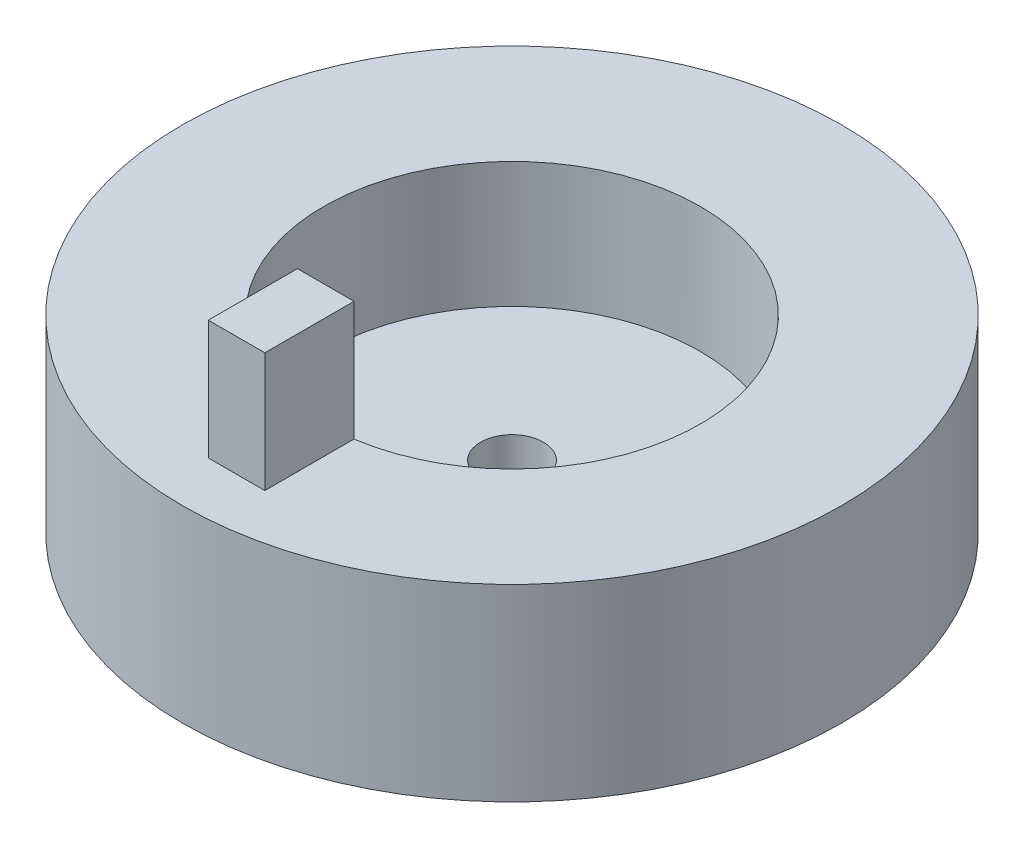
SolidWorks part; units mm, degrees
ref_plane "Front" through (0, 0, 0) normal (0, 0, 1) x (1, 0, 0)
ref_plane "Top" through (0, 0, 0) normal (0, 1, 0) x (1, 0, 0)
ref_plane "Right" through (0, 0, 0) normal (1, 0, 0) x (0, 0, -1)
sketch "Skizze1" plane through (0, 0, 0) normal (0, 1, 0) x (1, 0, 0)
  circle A0 centre (0, 0) radius 30
  circle A1 centre (0, 0) radius 52.5
  dimension "D1" = 60
  dimension "D2" = 105
extrude "Aufsatz-Linear austragen1" add sketch "Skizze1" along normal blind 20
sketch "Skizze2" plane through (0, 0, 0) normal (0, -1, 0) x (1, 0, 0)
  circle A0 centre (0, 0) radius 52.5
  circle A1 centre (0, 0) radius 5
  circle A2 centre (0, 0) radius 52.5 construction
  dimension "D1" = 10
extrude "Aufsatz-Linear austragen2" add sketch "Skizze2" along normal blind 10
sketch "Skizze3" plane through (0, 20, 0) normal (0, 1, 0) x (1, 0, 0)
  line L0 (0, 0) -> (0, -64.4242) construction
  line L6 (4.5, -29.6606) -> (-4.5, -29.6606)
  line L7 (-4.5, -29.6606) -> (-4.5, -43.8606)
  line L8 (-4.5, -43.8606) -> (4.5, -43.8606)
  line L10 (4.5, -29.6606) -> (4.5, -43.8606)
  circle A1 centre (0, 0) radius 30 construction
  point P16 (0, -43.8606)
  point P17 (0, -29.6606)
  dimension "D1" = 14.2
  dimension "D2" = 9
extrude "Aufsatz-Linear austragen3" add sketch "Skizze3" along normal blind 19
